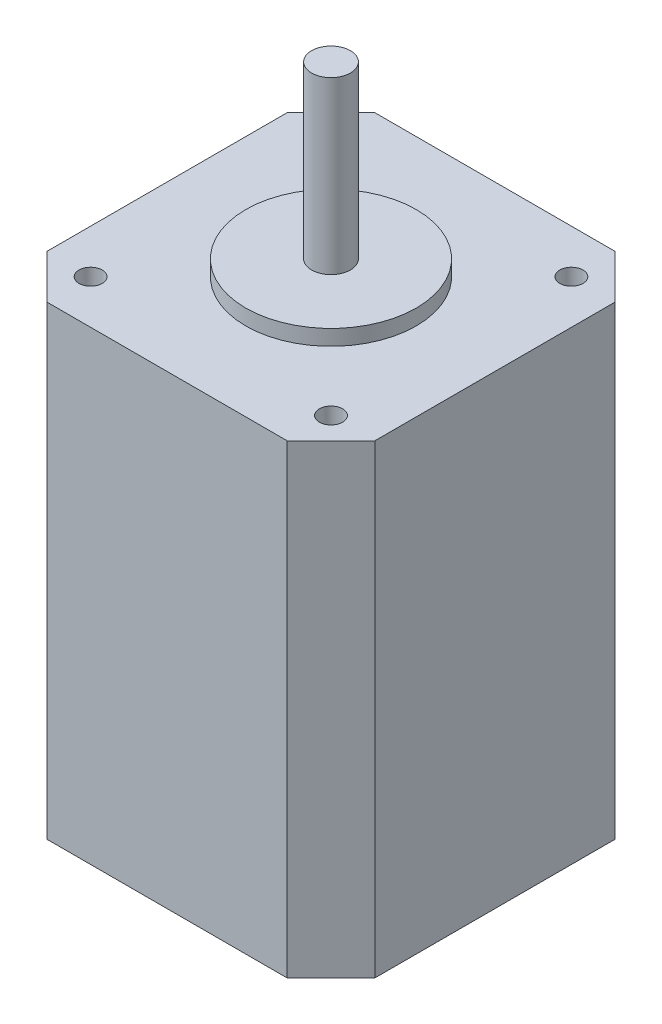
SolidWorks part; units mm, degrees
ref_plane "前基準面" through (0, 0, 0) normal (0, 0, 1) x (1, 0, 0)
ref_plane "上基準面" through (0, 0, 0) normal (0, 1, 0) x (1, 0, 0)
ref_plane "右基準面" through (0, 0, 0) normal (1, 0, 0) x (0, 0, -1)
sketch "草圖1" plane through (0, 0, 0) normal (0, 1, 0) x (1, 0, 0)
  line L0 (-15.5, -21.15) -> (-15.5, 21.15) construction
  line L1 (-15.5, 21.15) -> (15.5, 21.15)
  line L2 (-21.15, 15.5) -> (-21.15, -15.5)
  line L3 (-15.5, -21.15) -> (15.5, -21.15)
  line L4 (21.15, 15.5) -> (21.15, -15.5)
  line L5 (0, -21.15) -> (0, 21.15) construction
  line L6 (-21.15, 0) -> (21.15, 0) construction
  line L7 (15.5, -21.15) -> (15.5, 21.15) construction
  line L8 (-21.15, 15.5) -> (21.15, 15.5) construction
  line L9 (-21.15, -15.5) -> (21.15, -15.5) construction
  line L10 (-15.5, -21.15) -> (-21.15, -15.5)
  line L11 (15.5, -21.15) -> (21.15, -15.5)
  line L12 (-21.15, 15.5) -> (-15.5, 21.15)
  line L13 (15.5, 21.15) -> (21.15, 15.5)
  circle A0 centre (-15.5, 15.5) radius 1.5
  circle A1 centre (15.5, 15.5) radius 1.5
  circle A2 centre (15.5, -15.5) radius 1.5
  circle A3 centre (-15.5, -15.5) radius 1.5
  point P0 (0, 0)
  dimension "D3" = 3
  dimension "D1" = 42.3
  dimension "D2" = 42.3
  dimension "D4" = 31
  dimension "D5" = 31
  dimension "D6" = 45
  dimension "D7" = 225
  dimension "D8" = 135
extrude "填料-伸長1" add sketch "草圖1" along normal blind 60
sketch "草圖2" plane through (0, 60, 0) normal (0, 1, 0) x (1, 0, 0)
  circle A0 centre (0, 0) radius 11
  dimension "D1" = 22
extrude "填料-伸長2" add sketch "草圖2" along normal blind 2
sketch "草圖3" plane through (0, 62, 0) normal (0, 1, 0) x (1, 0, 0)
  circle A0 centre (0, 0) radius 2.5
  dimension "D1" = 5
extrude "填料-伸長3" add sketch "草圖3" along normal blind 22
